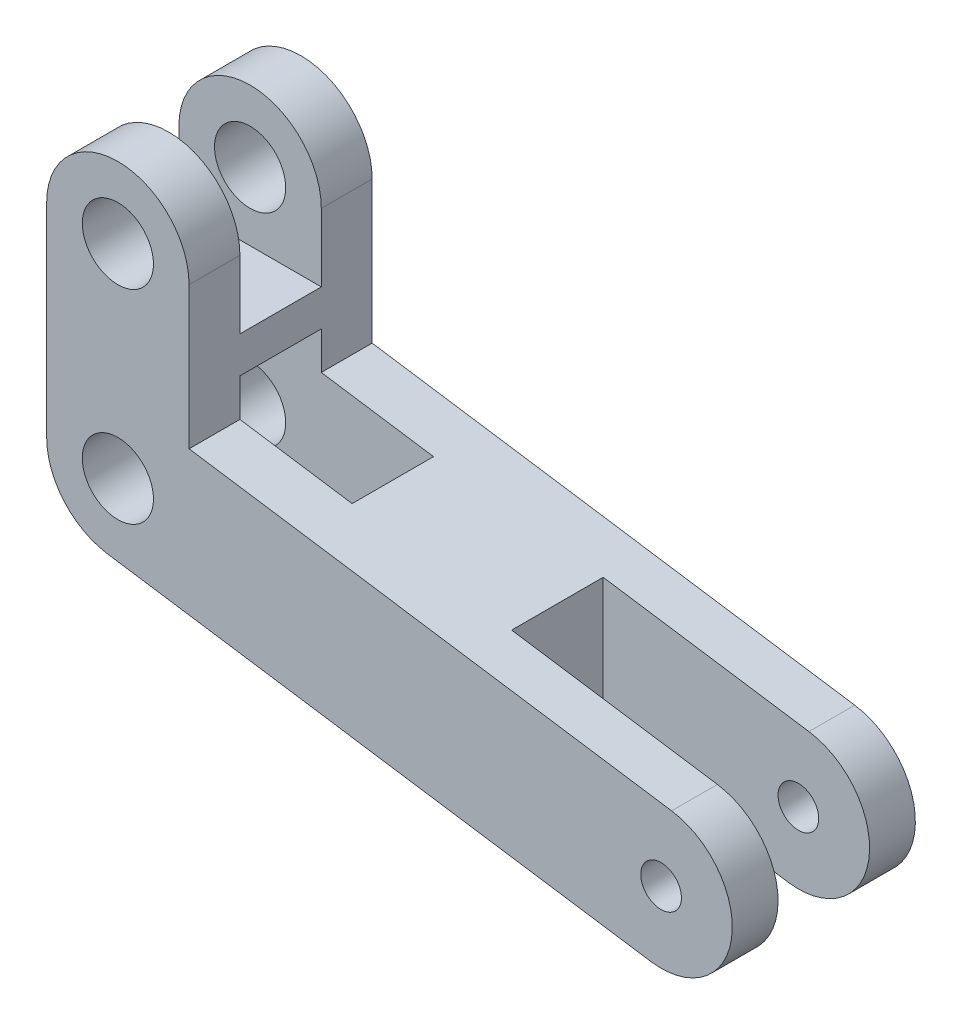
SolidWorks part; units mm, degrees
ref_plane "前视基准面" through (0, 0, 0) normal (0, 0, 1) x (1, 0, 0)
ref_plane "上视基准面" through (0, 0, 0) normal (0, 1, 0) x (1, 0, 0)
ref_plane "右视基准面" through (0, 0, 0) normal (1, 0, 0) x (0, 0, -1)
other "Configuration Table"
sketch "草图1" plane through (0, 0, 0) normal (0, 0, 1) x (1, 0, 0)
  line L0 (0, 10) -> (0, 1.75) construction
  line L1 (26.1835, -7.4614) -> (-0.5185, -3.4614)
  line L2 (-3.5, 10) -> (-3.5, 0)
  line L3 (3.5, 10) -> (3.5, 3.0147)
  line L8 (27.2206, -0.5386) -> (3.5, 3.0147)
  line L9 (26.7021, -3) -> (26.7021, -4) construction
  circle A0 centre (0, 0) radius 1.75
  arc A1 (-3.5, 0) -> (-0.5185, -3.4614) centre (0, 0) ccw
  arc A2 (3.5, 10) -> (-3.5, 10) centre (0, 10) ccw
  circle A4 centre (0, 10) radius 1.75
  arc A5 (26.1835, -7.4614) -> (27.2206, -0.5386) centre (26.7021, -4) ccw
  circle A6 centre (26.7021, -4) radius 1
  dimension "D1" = 10
  dimension "D2" = 3.5
  dimension "D3" = 7
  dimension "D8" = 2
  dimension "D4" = 27
  dimension "D5" = 4
extrude "凸台-拉伸1" add sketch "草图1" along normal mid plane 9
sketch "草图5" plane through (0, 0, 0) normal (0, 0, 1) x (1, 0, 0)
  line L1 (-5.6997, 16.4699) -> (3.5, 16.4699)
  line L2 (-5.6997, 16.4699) -> (-5.6997, 6.6567)
  line L3 (-5.6997, 6.6567) -> (3.5, 6.6567)
  line L4 (3.5, 16.4699) -> (3.5, 6.6567)
  line L5 (-5.6455, -5.6561) -> (9.0148, -5.6561)
  line L6 (-5.6455, -5.6561) -> (-5.6455, 4.8693)
  line L7 (-5.6455, 4.8693) -> (9.0148, 4.8693)
  line L8 (9.0148, -5.6561) -> (9.0148, 4.8693)
extrude "切除-拉伸3" cut sketch "草图5" against normal mid plane 4
sketch "草图6" plane through (0, 0, 0) normal (0, 0, 1) x (1, 0, 0)
  line L1 (36.2955, -10) -> (17.1087, -10)
  line L2 (36.2955, -10) -> (36.2955, 2)
  line L3 (36.2955, 2) -> (17.1087, 2)
  line L4 (17.1087, -10) -> (17.1087, 2)
  line L5 (36.2955, -10) -> (17.1087, 2) construction
  line L6 (36.2955, 2) -> (17.1087, -10) construction
  point P0 (26.7021, -4)
  dimension "D1" = 6
extrude "切除-拉伸4" cut sketch "草图6" against normal mid plane 4.5
